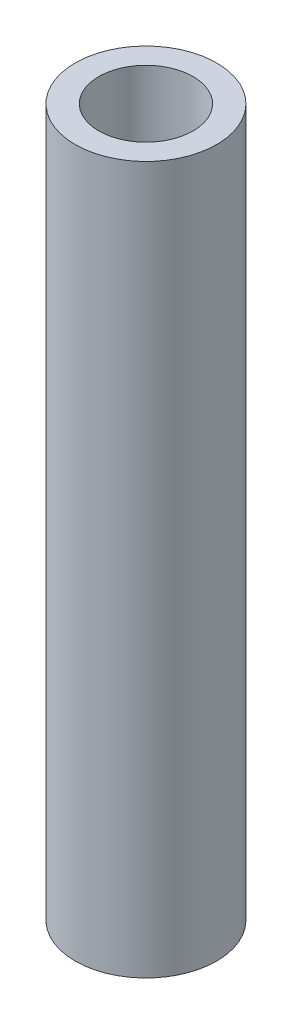
SolidWorks part; units mm, degrees
ref_plane "Front Plane" through (0, 0, 0) normal (0, 0, 1) x (1, 0, 0)
ref_plane "Top Plane" through (0, 0, 0) normal (0, 1, 0) x (1, 0, 0)
ref_plane "Right Plane" through (0, 0, 0) normal (1, 0, 0) x (0, 0, -1)
sketch "Sketch1" plane through (0, 0, 0) normal (0, 1, 0) x (1, 0, 0)
  circle A0 centre (0, 0) radius 3
  dimension "D1" = 6
extrude "Boss-Extrude1" add sketch "Sketch1" along normal blind 30
sketch "Sketch2" plane through (0, 30, 0) normal (0, 1, 0) x (1, 0, 0)
  circle A0 centre (0, 0) radius 2
  dimension "D1" = 4
extrude "Cut-Extrude1" cut sketch "Sketch2" against normal through all
